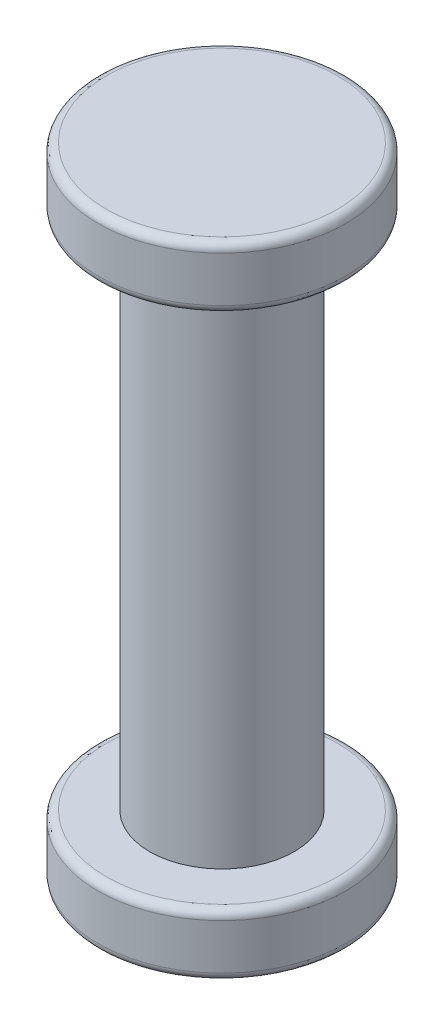
SolidWorks part; units mm, degrees
ref_plane "Front Plane" through (0, 0, 0) normal (0, 0, 1) x (1, 0, 0)
ref_plane "Top Plane" through (0, 0, 0) normal (0, 1, 0) x (1, 0, 0)
ref_plane "Right Plane" through (0, 0, 0) normal (1, 0, 0) x (0, 0, -1)
sketch "Sketch1" plane through (0, 0, 0) normal (0, 1, 0) x (1, 0, 0)
  circle A0 centre (0, 0) radius 1.75
  dimension "D1" = 3.5
extrude "Boss-Extrude1" add sketch "Sketch1" along normal mid plane 12.5
sketch "Sketch2" plane through (0, 0, 0) normal (0, 0, 1) x (1, 0, 0)
  line L0 (0, -7.75) -> (0, 7.75)
  line L1 (0, 7.75) -> (-2.8, 7.75)
  line L2 (-3, 7.55) -> (-3, 6.45)
  line L3 (-2.8, 6.25) -> (0, 6.25)
  line L4 (1.75, 6.25) -> (-1.75, 6.25) construction
  line L5 (0, 0) -> (2.6622, 0) construction
  line L6 (-2.8, -6.25) -> (0, -6.25)
  line L7 (-3, -7.55) -> (-3, -6.45)
  line L8 (0, -7.75) -> (-2.8, -7.75)
  arc A0 (-3, -7.55) -> (-2.8, -7.75) centre (-2.8, -7.55) ccw
  arc A1 (-3, -6.45) -> (-2.8, -6.25) centre (-2.8, -6.45) cw
  arc A2 (-2.8, 7.75) -> (-3, 7.55) centre (-2.8, 7.55) ccw
  arc A3 (-3, 6.45) -> (-2.8, 6.25) centre (-2.8, 6.45) ccw
  point P4 (0, 0)
  point P17 (-3, -7.75)
  point P20 (-3, -6.25)
  point P23 (-3, 7.75)
  point P26 (-3, 6.25)
  dimension "D3" = 0.2
  dimension "D1" = 3
  dimension "D2" = 1.5
revolve "Revolve1" add sketch "Sketch2" angle 360 about L0
